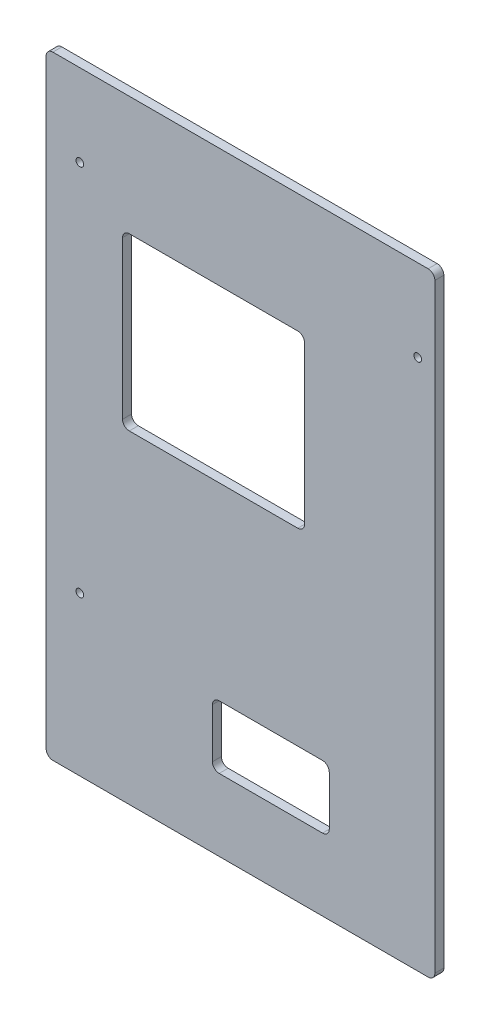
SolidWorks part; units mm, degrees
material "Verre"
ref_plane "Plan de face" through (0, 0, 0) normal (0, 0, 1) x (1, 0, 0)
ref_plane "Plan de dessus" through (0, 0, 0) normal (0, 1, 0) x (1, 0, 0)
ref_plane "Plan de droite" through (0, 0, 0) normal (1, 0, 0) x (0, 0, -1)
sketch "Esquisse1" plane through (0, 0, 0) normal (0, 0, 1) x (1, 0, 0)
  line L1 (0, 0) -> (173, 0)
  line L2 (0, 0) -> (0, 273)
  line L3 (0, 273) -> (173, 273)
  line L4 (173, 0) -> (173, 273)
  line L5 (74, 60) -> (126, 60)
  line L6 (74, 60) -> (74, 32)
  line L7 (74, 32) -> (126, 32)
  line L8 (126, 60) -> (126, 32)
  line L9 (34, 220) -> (115, 220)
  line L10 (34, 220) -> (34, 144)
  line L11 (34, 144) -> (115, 144)
  line L12 (115, 220) -> (115, 144)
  circle A0 centre (15, 236.5) radius 1.5
  circle A1 centre (165.38, 236.5) radius 1.5
  circle A2 centre (15, 70.5) radius 1.5
  dimension "D5" = 3
  dimension "D8" = 3
  dimension "D11" = 3
  dimension "D1" = 173
  dimension "D2" = 273
  dimension "D3" = 36.5
  dimension "D4" = 15
  dimension "D6" = 7.62
  dimension "D7" = 36.5
  dimension "D9" = 70.5
  dimension "D10" = 15
  dimension "D12" = 74
  dimension "D13" = 52
  dimension "D14" = 28
  dimension "D15" = 32
  dimension "D16" = 34
  dimension "D17" = 81
  dimension "D18" = 144
  dimension "D19" = 76
extrude "Boss.-Extru.1" add sketch "Esquisse1" along normal blind 4
hole_wizard "Dégagement M31" positions "Esquisse2" profile "Esquisse3" hole size "M3" standard "ISO" end condition through all
sketch "Esquisse2" plane through (0, 0, 4) normal (0, 0, 1) x (1, 0, 0)
  point P0 (15, 236.5)
  point P3 (15, 70.5)
  point P6 (165.38, 236.5)
sketch "Esquisse3" plane through (15, 236.5, 4) normal (1, 0, 0) x (0, -1, 0)
  line L0 (0, 0) -> (0, 4)
  line L1 (0, 4) -> (1.7, 4)
  line L2 (1.7, 4) -> (1.7, 0)
  line L5 (1.7, 0) -> (0, 0)
  line L11 (0, -6.35) -> (0, 107.95) construction
  dimension "Diamètre du perçage jusqu'au prochain" = 3.4
  dimension "Profondeur du perçage jusqu'au prochain" = 4
fillet "Congé1" radius 3 12 edges at (0, 0, 2) (173, 0, 2) (126, 32, 2) (74, 32, 2) (126, 60, 2) (74, 60, 2) (115, 144, 2) (34, 144, 2) (115, 220, 2) (34, 220, 2) (173, 273, 2) (0, 273, 2)
